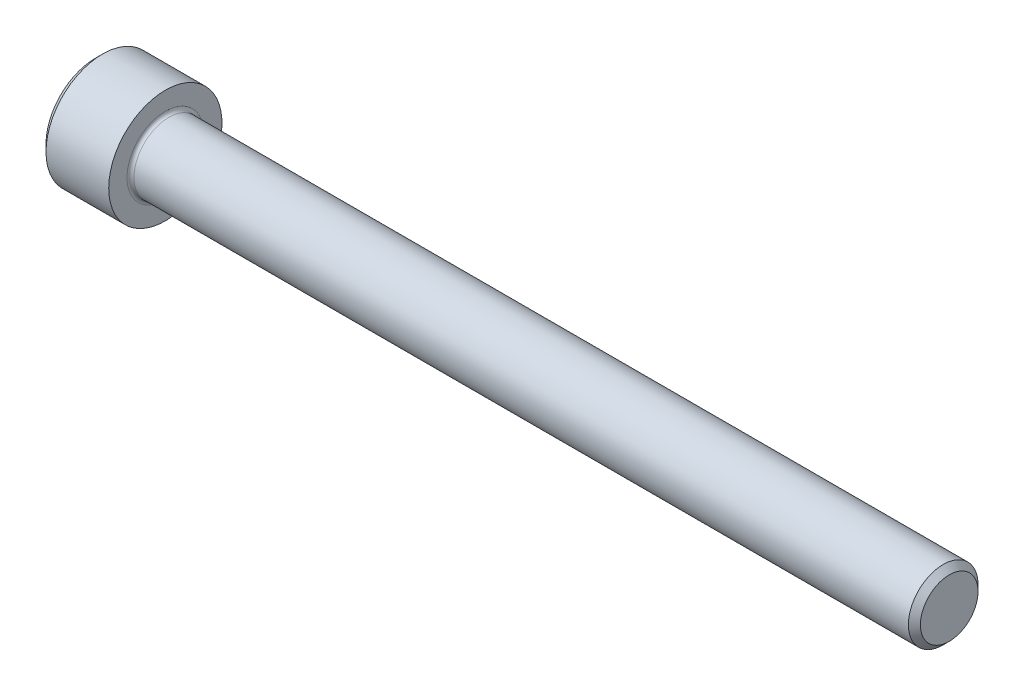
SolidWorks part; units mm, degrees
revolve "Base-Revolve" add sketch "BodySke"
sketch "BodySke" plane through (0, 0, 0) normal (0, 0, 1) x (1, 0, 0)
  line L0 (0, 0) -> (0, 5.7)
  line L1 (0.8, 6.5) -> (8, 6.5)
  line L2 (8, 6.5) -> (8, 4)
  line L3 (8, 4) -> (97.3095, 4)
  line L4 (98, 3.3095) -> (98, 0)
  line L5 (98, 0) -> (0, 0)
  line L6 (-31.75, 0) -> (127, 0) construction
  line L7 (0, 5.7) -> (0.8, 6.5)
  line L8 (98, 3.3095) -> (97.3095, 4)
  line L9 (0, -5.7) -> (0.8, -6.5) construction
  line L10 (98, -3.3095) -> (97.3095, -4) construction
  line L11 (9.25, 9.525) -> (9.25, 3.175) construction
  line L12 (70, 9.525) -> (70, 3.175) construction
  line L13 (48, 9.525) -> (48, 3.175) construction
  dimension "Diameter" = 8
  dimension "Head_ht" = 8
  dimension "Length" = 90
  dimension "Body_ch_ang" = 45
  dimension "Head_dia" = 13
  dimension "Head_ch_ang" = 45
  dimension "Minor_dia" = 6.619
  dimension "Advance" = 1.25
  dimension "Thread_nom" = 28
  dimension "Thread_length" = 50
  dimension "Head_ch_ht" = 0.8
cosmetic thread "ThreadCosmetic" [suppressed]
fillet "Fillet1" radius 0.4 1 edges at (8, 0, 4)
ref_plane "Plane1" through (0, 0, 0) normal (0, 0, 1) x (1, 0, 0)
ref_plane "Plane2" through (0, 0, 0) normal (0, 1, 0) x (1, 0, 0)
ref_plane "Plane3" through (0, 0, 0) normal (1, 0, 0) x (0, 0, -1)
sketch "Sketch2" plane through (0, 0, 0) normal (0, 0, 1) x (1, 0, 0)
  line L0 (0, 3.0475) -> (4, 3.0475)
  line L1 (4, 3.0475) -> (5.7595, 0)
  line L2 (-31.75, 0) -> (127, 0) construction
  line L3 (5.7595, 0) -> (0, 0)
  line L4 (0, 0) -> (0, 3.0475)
  line L5 (0, 5.7) -> (0, -5.7) construction
  line L6 (0, 0) -> (47.625, 0) construction
  line L7 (8, -6.5) -> (8, 6.5) construction
  dimension "D1" = 3.0475
  dimension "D2" = 60
revolve "Hex-PreBroach" cut sketch "Sketch2" angle 360 about L6
sketch "Sketch3" plane through (0, 0, 0) normal (-1, 0, 0) x (0, 0.5, 0.866)
  line L0 (1.7595, 3.0475) -> (-1.7595, 3.0475)
  line L1 (-1.7595, 3.0475) -> (-3.5189, 0)
  line L2 (1.7595, 3.0475) -> (3.5189, 0)
  line L3 (1.7595, -3.0475) -> (3.5189, 0)
  line L4 (1.7595, -3.0475) -> (-1.7595, -3.0475)
  line L5 (-1.7595, -3.0475) -> (-3.5189, 0)
  dimension "D1" = 3.0475
  dimension "D2" = 3.0475
  dimension "Hex_size" = 6.095
extrude "Hex" cut sketch "Sketch3" against normal blind 4
sketch "Sketch4" plane through (0, 0, 0) normal (-1, 0, 0) x (0, 0, 1)
  line L0 (0, 0) -> (3.7846, 0)
  line L1 (0, 0) -> (6.1484, 3.5498) construction
  line L2 (0, 0) -> (1.8923, 3.2776)
  line L3 (3.1235, 0.8061) -> (3.6229, 1.0945)
  line L4 (2.2599, 2.3019) -> (2.7593, 2.5903)
  arc A0 (3.1235, 0.8061) -> (2.2599, 2.3019) centre (0, 0) ccw
  arc A1 (3.7846, 0) -> (3.6229, 1.0945) centre (0, 0) ccw
  arc A2 (1.8923, 3.2776) -> (2.7593, 2.5903) centre (0, 0) cw
  dimension "D1" = 30
  dimension "D2" = 60
  dimension "Spline_p_dim" = 1.7272
  dimension "D3" = 0.8636
extrude "Spline" [suppressed] cut sketch "Sketch4" against normal blind 4
pattern_circular "CirPattern1" [suppressed] count 6 every 60
sketch "Sketch5" plane through (0, 0, 0) normal (0, 0, 1) x (1, 0, 0)
  line L0 (-31.75, 0) -> (127, 0) construction
  line L2 (0, 5.7) -> (0, -5.7) construction
  circle A0 centre (2.7, 0) radius 0.675
  dimension "Drilled_hole_dia" = 1.35
  dimension "Drilled_hole_loc" = 2.7
extrude "Hole" [suppressed] cut sketch "Sketch5" against normal through all and the other way through all
pattern_circular "Drilled-4" [suppressed] count 2 every 60
pattern_circular "Drilled-6" [suppressed] count 3 every 60
sketch "ThdSchSke" plane through (0, 0, 0) normal (0, 0, 1) x (1, 0, 0)
  line L0 (70, -3.3095) -> (69.5165, -4)
  line L1 (70, -3.3095) -> (70.4835, -4)
  line L2 (70.4835, -4) -> (70.4835, -5)
  line L3 (-3.175, 0) -> (5.1513, 0) construction
  line L5 (70.4835, -5) -> (69.5165, -5)
  line L6 (69.5165, -5) -> (69.5165, -4)
  line L7 (0, 5.7) -> (0, -5.7) construction
  dimension "Thread_minor" = 6.619
  dimension "Diameter" = 8
revolve "ThreadSchematic" [suppressed] cut sketch "ThdSchSke" angle 360 about L3
pattern_linear "ThdSchPat" [suppressed]
equation "\"D2@Sketch3\" = \"Hex_size@Sketch3\" / 2"
equation "\"D1@Sketch3\" = \"Hex_size@Sketch3\" / 2"
equation "\"D1@Sketch2\" = \"Hex_size@Sketch3\" / 2"
equation "\"D3@Sketch4\" = \"Spline_p_dim@Sketch4\" / 2"
equation "\"Thread_minor@ThreadCosmetic\"  =  \"Minor_dia@BodySke\""
equation "\"D2@CirPattern1\" = 360 / \"Num_teeth@CirPattern1\""
equation "\"Wall_thickness@Sketch2\" = \"Head_ht@BodySke\" - \"Key_eng@Hex\""
equation "\"Thread_length@ThreadCosmetic\" = ((sgn( (\"Length@BodySke\" - \"Advance@BodySke\" ) - \"Thread_nom@BodySke\" )-1)*( (\"Length@BodySke\" - \"Advance@BodySke\" ) - \"Thread_nom@BodySke\" ))/-2+ \"Thread_nom@BodySke\""
equation "\"Thread_minor@ThdSchSke\" = \"Minor_dia@BodySke\""
equation "\"Diameter@ThdSchSke\" = \"Diameter@BodySke\""
equation "\"Overcut@ThdSchSke\" = \"Diameter@BodySke\" * 1.25"
equation "\"Start@ThdSchSke\" = \"Head_ht@BodySke\" + \"Length@BodySke\" - \"Thread_length@ThreadCosmetic\"  '---Non-countersunk---"
equation "\"Num_threads@ThdSchPat\" = int( \"Thread_length@ThreadCosmetic\" / \"Advance@BodySke\" + 0.999 )  + 1"
equation "\"Advance@ThdSchPat\" = \"Thread_length@ThreadCosmetic\" /  (\"Num_threads@ThdSchPat\" - 1) 'relax it"
equation "\"Num_threads@ThdSchPat\" = \"Num_threads@ThdSchPat\" - sgn( \"Num_threads@ThdSchPat\" - 1) '---chamfered tips only---"
